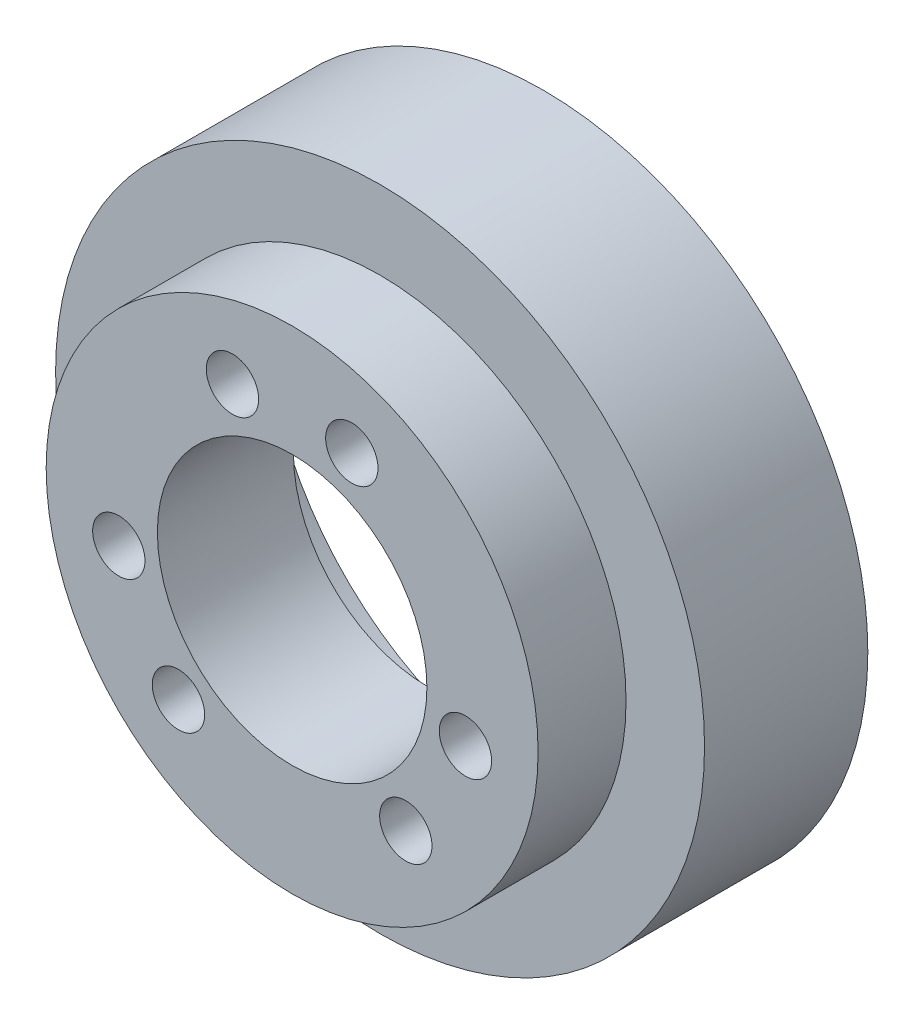
SolidWorks part; units mm, degrees
ref_plane "Front Plane" through (0, 0, 0) normal (0, 0, 1) x (1, 0, 0)
ref_plane "Top Plane" through (0, 0, 0) normal (0, 1, 0) x (1, 0, 0)
ref_plane "Right Plane" through (0, 0, 0) normal (1, 0, 0) x (0, 0, -1)
sketch "Sketch1" plane through (0, 0, 0) normal (0, 0, 1) x (1, 0, 0)
  circle A0 centre (0, 0) radius 31
  dimension "D1" = 62
extrude "Boss-Extrude1" add sketch "Sketch1" along normal blind 15.6
sketch "Sketch2" plane through (0, 0, 15.6) normal (0, 0, 1) x (1, 0, 0)
  circle A0 centre (0, 0) radius 23.5
  dimension "D1" = 47
extrude "Boss-Extrude2" add sketch "Sketch2" along normal offset from surface (8.4 mm away) 24 up to face at (31, 0, 0)
sketch "Sketch3" plane through (0, 0, 24) normal (0, 0, 1) x (1, 0, 0)
  circle A0 centre (0, 0) radius 12.875
  dimension "D1" = 25.75
extrude "Cut-Extrude1" cut sketch "Sketch3" against normal through all
sketch "Sketch4" plane through (0, 0, 0) normal (0, 0, -1) x (-1, 0, 0)
  circle A0 centre (0, 0) radius 26.625
  dimension "D1" = 53.25
extrude "Cut-Extrude2" cut sketch "Sketch4" against normal blind 11
sketch "Sketch5" plane through (0, 0, 24) normal (0, 0, 1) x (1, 0, 0)
  line L0 (0, 0) -> (0, 23.5) construction
  circle A0 centre (5.7, 15.8301) radius 2.45
  circle A1 centre (-5.7, 15.8301) radius 2.45
  circle A2 centre (0, 0) radius 23.5 construction
  circle A4 centre (0, 0) radius 12.875 construction
  dimension "D1" = 4.9
  dimension "D2" = 6.5
  dimension "D3" = 1.5
hole_wizard "M6x1.0 Tapped Hole1" positions "Sketch6" profile "Sketch7" tap size "M6x1.0" standard "ANSI Metric" end condition through all
sketch "Sketch6" plane through (0, 0, 24) normal (0, 0, 1) x (1, 0, 0)
  point P0 (-5.7, 15.8301)
  point P3 (5.7, 15.8301)
sketch "Sketch7" plane through (-5.7, 15.8301, 24) normal (1, 0, 0) x (0, -1, 0)
  line L0 (0, 0) -> (0, 24)
  line L1 (0, 24) -> (2.5, 24)
  line L2 (2.5, 24) -> (2.5, 0)
  line L5 (2.5, 0) -> (0, 0)
  line L11 (0, -6.35) -> (0, 107.95) construction
  dimension "Thru Tap Drill Dia." = 5
  dimension "Thru Tap Drill Depth" = 24
cosmetic thread "Hole Thread1" parameters "D2"=6
cosmetic thread "Hole Thread2" parameters "D2"=6
pattern_circular "CirPattern1" count 3 over 360 about axis through (0, 0, 0) along (0, 0, 1) of "M6x1.0 Tapped Hole1"
cosmetic thread "Hole Thread3" parameters "D2"=6
cosmetic thread "Hole Thread4" parameters "D2"=6
cosmetic thread "Hole Thread5" parameters "D2"=6
cosmetic thread "Hole Thread6" parameters "D2"=6
